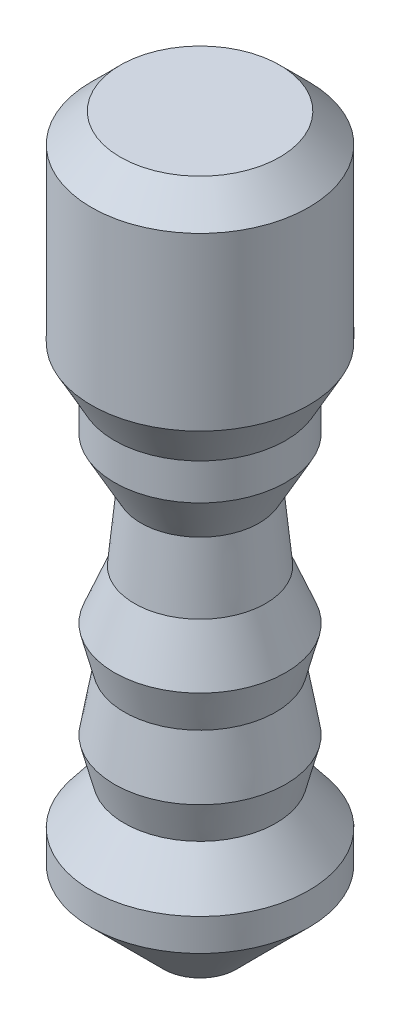
SolidWorks part; units mm, degrees
ref_plane "Front Plane" through (0, 0, 0) normal (0, 0, 1) x (1, 0, 0)
ref_plane "Top Plane" through (0, 0, 0) normal (0, 1, 0) x (1, 0, 0)
ref_plane "Right Plane" through (0, 0, 0) normal (1, 0, 0) x (0, 0, -1)
sketch "Sketch1" plane through (0, 0, 0) normal (0, 1, 0) x (1, 0, 0)
  circle A0 centre (0, 0) radius 7.5
  dimension "D1" = 15
extrude "Boss-Extrude1" add sketch "Sketch1" along normal blind 50
chamfer "Chamfer1" distance 5 angle 45 1 edges at (0, 0, 7.5)
chamfer "Chamfer2" distance 2 angle 45 1 edges at (0, 50, 7.5)
sketch "Sketch2" plane through (0, 0, 0) normal (0, 0, 1) x (1, 0, 0)
  line L0 (7.5, 36.1901) -> (5.9086, 33.2853)
  line L1 (7.5, 5) -> (7.5, 48) construction
  line L2 (5.9086, 33.2853) -> (5.9086, 30.7766)
  line L3 (5.9086, 30.7766) -> (4.081, 27.4407)
  line L4 (4.081, 27.4407) -> (4.5222, 22.8544)
  line L5 (4.5222, 22.8544) -> (5.9086, 19.4215)
  line L6 (5.9086, 19.4215) -> (5.2154, 16.7147)
  line L7 (5.2154, 16.7147) -> (5.9086, 12.7536)
  line L8 (5.9086, 12.7536) -> (5.2256, 10.0866)
  line L9 (5.2256, 10.0866) -> (7.5, 7.2081)
  line L10 (7.5, 36.1901) -> (18.32, 16.7147)
  line L11 (18.32, 16.7147) -> (7.5, 7.2081)
  line L12 (0, 0) -> (0, 13.2818) construction
revolve "Cut-Revolve1" cut sketch "Sketch2" angle 360 about L12
